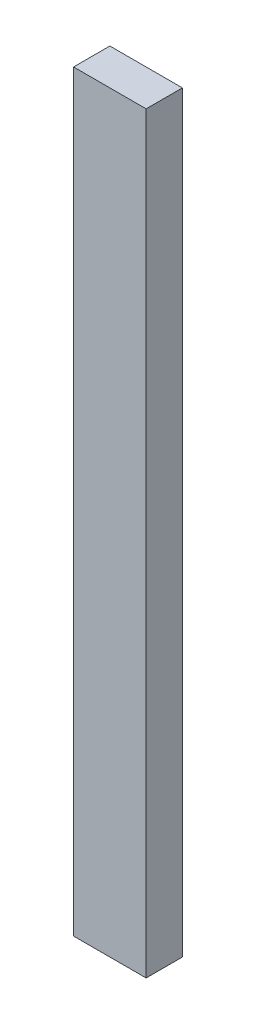
SolidWorks part; units mm, degrees
material "ABS PC"
ref_plane "Front Plane" through (0, 0, 0) normal (0, 0, 1) x (1, 0, 0)
ref_plane "Top Plane" through (0, 0, 0) normal (0, 1, 0) x (1, 0, 0)
ref_plane "Right Plane" through (0, 0, 0) normal (1, 0, 0) x (0, 0, -1)
sketch "Sketch1" plane through (0, 0, 0) normal (0, 1, 0) x (1, 0, 0)
  line L1 (0, 0) -> (25.4, 0)
  line L2 (0, 0) -> (0, 12.7)
  line L3 (0, 12.7) -> (25.4, 12.7)
  line L4 (25.4, 0) -> (25.4, 12.7)
  dimension "D1" = 25.4
  dimension "D2" = 12.7
extrude "Boss-Extrude1" add sketch "Sketch1" along normal blind 263.525
